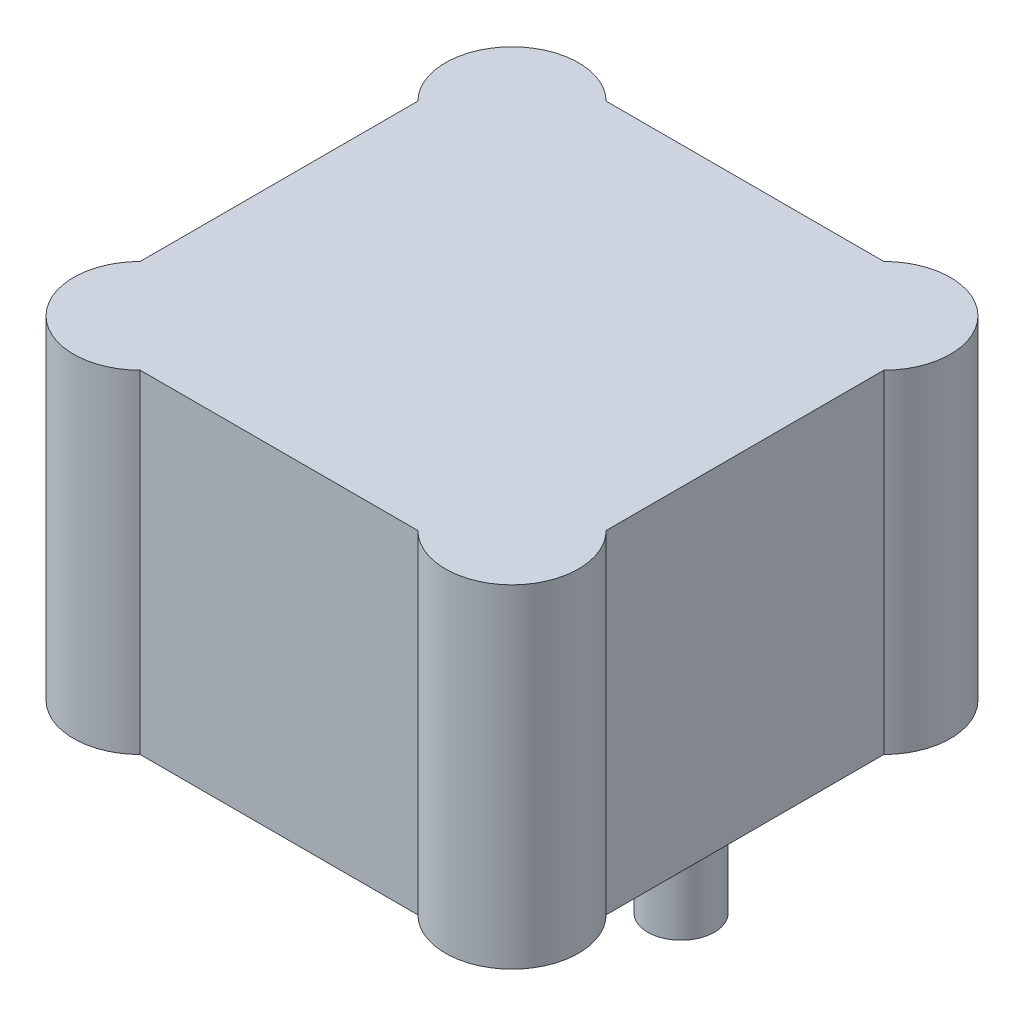
SolidWorks part; units mm, degrees
ref_plane "Front Plane" through (0, 0, 0) normal (0, 0, 1) x (1, 0, 0)
ref_plane "Top Plane" through (0, 0, 0) normal (0, 1, 0) x (1, 0, 0)
ref_plane "Right Plane" through (0, 0, 0) normal (1, 0, 0) x (0, 0, -1)
other "Configuration Table"
sketch "Sketch1" plane through (0, 0, 0) normal (0, 1, 0) x (1, 0, 0)
  line L1 (-4.1716, -7) -> (4.1716, -7)
  line L2 (-7, -4.1716) -> (-7, 4.1716)
  line L3 (-4.1716, 7) -> (4.1716, 7)
  line L4 (7, -4.1716) -> (7, 4.1716)
  line L5 (-7, -7) -> (7, 7) construction
  line L6 (-7, 7) -> (7, -7) construction
  line L7 (7, -7) -> (-7, -7) construction
  line L8 (7, -7) -> (7, 7) construction
  line L9 (7, 7) -> (-7, 7) construction
  line L10 (-7, -7) -> (-7, 7) construction
  line L11 (7, -7) -> (-7, 7) construction
  line L12 (7, 7) -> (-7, -7) construction
  arc A4 (-4.1716, 7) -> (-7, 4.1716) centre (-5.5858, 5.5858) ccw
  arc A5 (7, 4.1716) -> (4.1716, 7) centre (5.5858, 5.5858) ccw
  arc A6 (4.1716, -7) -> (7, -4.1716) centre (5.5858, -5.5858) ccw
  arc A7 (-7, -4.1716) -> (-4.1716, -7) centre (-5.5858, -5.5858) ccw
  point P0 (0, 0)
  point P19 (0, 0)
  dimension "D1" = 14
  dimension "D2" = 4
extrude "Boss-Extrude1" add sketch "Sketch1" along normal blind 10
sketch "Sketch2" plane through (0, 0, 0) normal (0, -1, 0) x (1, 0, 0)
  line L0 (-5.08, 0) -> (0, 0) construction
  line L1 (0, 0) -> (5.08, 0) construction
  circle A0 centre (0, 0) radius 2
  circle A1 centre (-5.08, 0) radius 1
  circle A2 centre (5.08, 0) radius 1
  dimension "D1" = 5.08
  dimension "D2" = 4
  dimension "D3" = 2
extrude "Boss-Extrude2" add sketch "Sketch2" along normal blind 3
